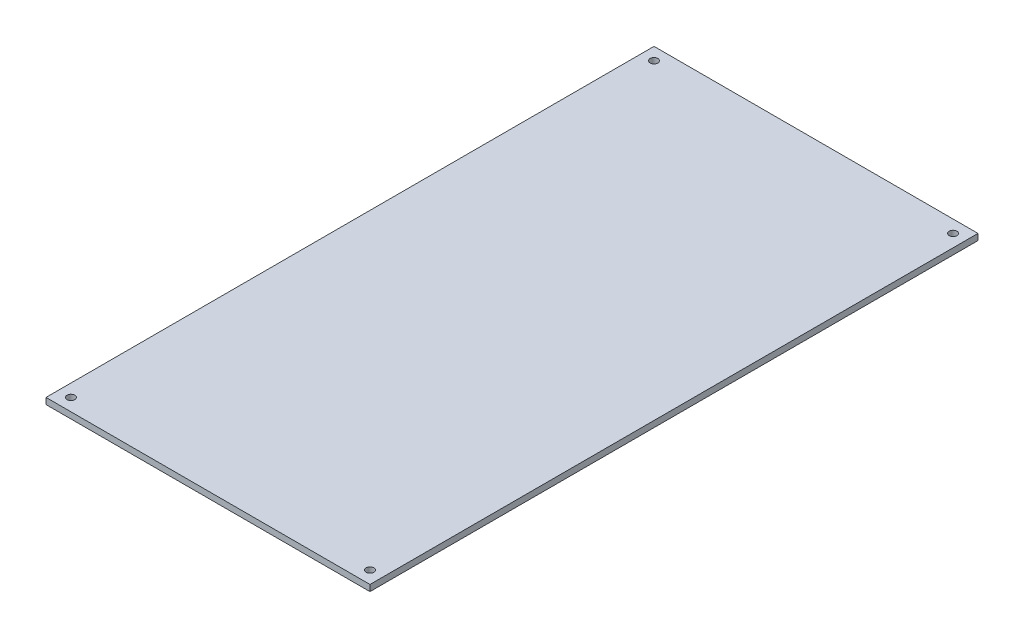
SolidWorks part; units mm, degrees
ref_plane "Front Plane" through (0, 0, 0) normal (0, 0, 1) x (1, 0, 0)
ref_plane "Top Plane" through (0, 0, 0) normal (0, 1, 0) x (1, 0, 0)
ref_plane "Right Plane" through (0, 0, 0) normal (1, 0, 0) x (0, 0, -1)
sketch "Sketch1" plane through (0, -91.8972, 0) normal (0, 1, 0) x (1, 0, 0)
  line L1 (-799.2, 626.1453) -> (-469, 626.1453)
  line L2 (-799.2, 626.1453) -> (-799.2, 6.4452)
  line L3 (-799.2, 6.4452) -> (-469, 6.4452)
  line L4 (-469, 626.1453) -> (-469, 6.4452)
  circle A0 centre (-786.5, 19.1452) radius 3.1293 construction
  circle A1 centre (-481.7, 19.1453) radius 3.9687 construction
  circle A2 centre (-481.7, 19.1453) radius 3.1293 construction
  circle A3 centre (-786.5, 613.4453) radius 3.1293 construction
  circle A4 centre (-481.7, 613.4453) radius 3.9688 construction
  circle A5 centre (-481.7, 613.4453) radius 3.9688
  circle A6 centre (-786.5, 613.4453) radius 3.9688 construction
  circle A7 centre (-786.5, 613.4453) radius 3.9688
  circle A8 centre (-786.5, 19.1452) radius 3.9687 construction
  circle A9 centre (-786.5, 19.1452) radius 3.9687
  circle A10 centre (-481.7, 19.1453) radius 3.9687
extrude "Boss-Extrude1" add sketch "Sketch1" along normal blind 6.35
